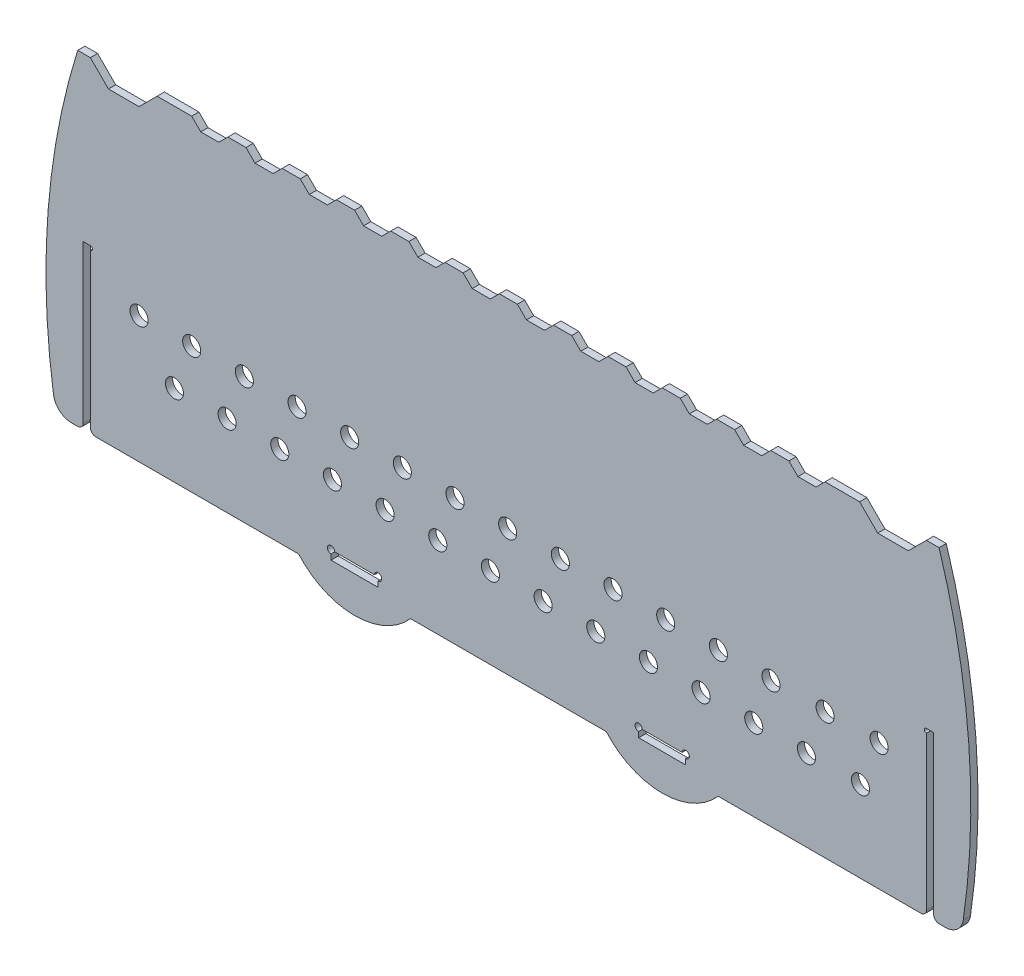
SolidWorks part; units mm, degrees
ref_plane "Спереди" through (0, 0, 0) normal (0, 0, 1) x (1, 0, 0)
ref_plane "Сверху" through (0, 0, 0) normal (0, 1, 0) x (1, 0, 0)
ref_plane "Справа" through (0, 0, 0) normal (1, 0, 0) x (0, 0, -1)
sketch "Эскиз1" plane through (0, 0, 0) normal (0, 0, 1) x (1, 0, 0)
  line L0 (152, 6) -> (178, 6)
  line L1 (8.5269, 0) -> (12, 0)
  line L2 (152, 6) -> (152, 9)
  line L3 (55.8972, 180) -> (45.8972, 170)
  line L4 (178, 6) -> (178, 9)
  line L5 (154, 11) -> (176, 11)
  line L6 (15, 3) -> (15, 90)
  line L7 (485, 3) -> (485, 90)
  line L8 (19, 87.6915) -> (19, 3)
  line L9 (481, 87.6915) -> (481, 3)
  line L14 (322, 6) -> (348, 6)
  line L15 (22, 0) -> (134.0741, 0)
  line L16 (324, 11) -> (346, 11)
  line L17 (195.9259, 0) -> (304.0741, 0)
  line L18 (485, 90) -> (481, 90)
  line L19 (365.9259, 0) -> (478, 0)
  line L20 (444.1028, 180) -> (454.1028, 170)
  line L21 (488, 0) -> (491.4731, 0)
  line L22 (348, 6) -> (348, 9)
  line L25 (19, 180) -> (29, 170)
  line L26 (481, 180) -> (471, 170)
  line L27 (19, 180) -> (12, 180)
  line L28 (481, 180) -> (488, 180)
  line L29 (19, 90) -> (15, 90)
  line L30 (322, 6) -> (322, 9)
  line L119 (245, 180) -> (255, 180)
  line L120 (105, 180) -> (110, 175)
  line L122 (180, 175) -> (170, 175)
  line L127 (150, 175) -> (140, 175)
  line L128 (300, 175) -> (290, 175)
  line L129 (345, 180) -> (350, 175)
  line L130 (155, 180) -> (165, 180)
  line L131 (185, 180) -> (195, 180)
  line L133 (75, 180) -> (80, 175)
  line L134 (125, 180) -> (120, 175)
  line L137 (345, 180) -> (335, 180)
  line L140 (215, 180) -> (210, 175)
  line L142 (285, 180) -> (290, 175)
  line L146 (215, 180) -> (225, 180)
  line L147 (270, 175) -> (260, 175)
  line L150 (390, 175) -> (380, 175)
  line L151 (375, 180) -> (380, 175)
  line L153 (444.1028, 180) -> (425, 180)
  line L156 (155, 180) -> (150, 175)
  line L160 (405, 180) -> (395, 180)
  line L164 (365, 180) -> (360, 175)
  line L165 (285, 180) -> (275, 180)
  line L166 (90, 175) -> (80, 175)
  line L167 (255, 180) -> (260, 175)
  line L168 (120, 175) -> (110, 175)
  line L170 (471, 170) -> (454.1028, 170)
  line L171 (375, 180) -> (365, 180)
  line L172 (55.8972, 180) -> (75, 180)
  line L173 (165, 180) -> (170, 175)
  line L174 (210, 175) -> (200, 175)
  line L175 (305, 180) -> (300, 175)
  line L176 (330, 175) -> (320, 175)
  line L177 (360, 175) -> (350, 175)
  line L179 (125, 180) -> (135, 180)
  line L182 (405, 180) -> (410, 175)
  line L183 (420, 175) -> (410, 175)
  line L187 (245, 180) -> (240, 175)
  line L191 (315, 180) -> (320, 175)
  line L193 (29, 170) -> (45.8972, 170)
  line L194 (135, 180) -> (140, 175)
  line L196 (425, 180) -> (420, 175)
  line L197 (185, 180) -> (180, 175)
  line L199 (240, 175) -> (230, 175)
  line L204 (275, 180) -> (270, 175)
  line L205 (95, 180) -> (90, 175)
  line L206 (395, 180) -> (390, 175)
  line L208 (195, 180) -> (200, 175)
  line L209 (225, 180) -> (230, 175)
  line L210 (335, 180) -> (330, 175)
  line L211 (95, 180) -> (105, 180)
  line L215 (315, 180) -> (305, 180)
  arc A0 (15, 3) -> (12, 0) centre (12, 3) cw
  arc A1 (19, 3) -> (22, 0) centre (22, 3) ccw
  arc A2 (481, 3) -> (478, 0) centre (478, 3) cw
  arc A3 (488, 0) -> (485, 3) centre (488, 3) cw
  circle A4 centre (45.8972, 70) radius 5
  circle A5 centre (65.4662, 45) radius 5
  circle A6 centre (75, 70) radius 5
  circle A7 centre (94.569, 45) radius 5
  circle A8 centre (104.1028, 70) radius 5
  circle A9 centre (123.6717, 45) radius 5
  circle A10 centre (133.2055, 70) radius 5
  circle A11 centre (152.7745, 45) radius 5
  circle A12 centre (162.3083, 70) radius 5
  circle A13 centre (181.8772, 45) radius 5
  circle A14 centre (191.411, 70) radius 5
  circle A15 centre (210.98, 45) radius 5
  circle A16 centre (220.5138, 70) radius 5
  circle A17 centre (240.0827, 45) radius 5
  circle A18 centre (249.6165, 70) radius 5
  circle A19 centre (269.1855, 45) radius 5
  circle A20 centre (278.7193, 70) radius 5
  circle A21 centre (298.2882, 45) radius 5
  circle A22 centre (307.822, 70) radius 5
  circle A23 centre (327.391, 45) radius 5
  circle A24 centre (336.9248, 70) radius 5
  circle A25 centre (356.4937, 45) radius 5
  circle A26 centre (366.0275, 70) radius 5
  circle A27 centre (385.5965, 45) radius 5
  circle A28 centre (395.1303, 70) radius 5
  circle A29 centre (414.6992, 45) radius 5
  circle A30 centre (425, 70) radius 5
  circle A31 centre (444.569, 45) radius 5
  circle A32 centre (454.8697, 70) radius 5
  arc A33 (134.0741, 0) -> (195.9259, 0) centre (165, 27.1575) ccw
  arc A34 (304.0741, 0) -> (365.9259, 0) centre (335, 27.1575) ccw
  arc A35 (12, 180) -> (-1.3647, 8.5313) centre (379.5877, 65.0942) ccw
  arc A36 (488, 180) -> (501.3647, 8.5313) centre (120.4123, 65.0942) cw
  arc A37 (-1.3647, 8.5313) -> (8.5269, 0) centre (8.5269, 10) ccw
  arc A38 (501.3647, 8.5313) -> (491.4731, 0) centre (491.4731, 10) cw
  arc A39 (19, 87.6915) -> (19, 90) centre (19, 88.8457) ccw
  arc A40 (178, 9) -> (176, 11) centre (178, 11) ccw
  arc A41 (481, 87.6915) -> (481, 90) centre (481, 88.8457) cw
  arc A42 (154, 11) -> (152, 9) centre (152, 11) ccw
  arc A43 (348, 9) -> (346, 11) centre (348, 11) ccw
  arc A44 (324, 11) -> (322, 9) centre (322, 11) ccw
  point P34 (485, 0)
  point P105 (0, 0)
  point P108 (500, 0)
extrude "Бобышка-Вытянуть1" add sketch "Эскиз1" along normal blind 4
